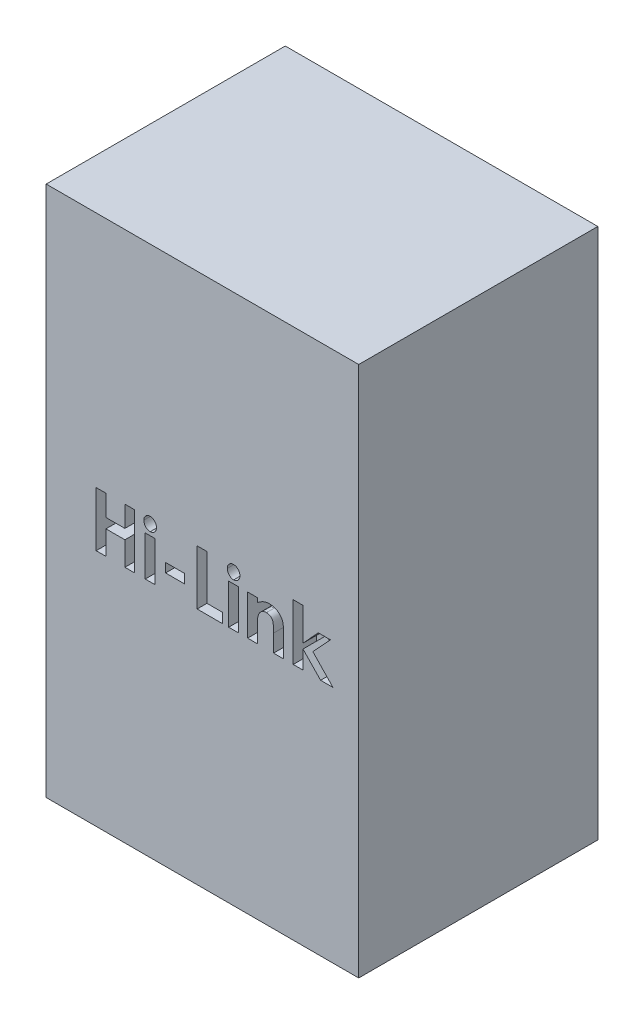
SolidWorks part; units mm, degrees
ref_plane "Plano frontal" through (0, 0, 0) normal (0, 0, 1) x (1, 0, 0)
ref_plane "Plano superior" through (0, 0, 0) normal (0, 1, 0) x (1, 0, 0)
ref_plane "Plano direito" through (0, 0, 0) normal (1, 0, 0) x (0, 0, -1)
sketch "Esboço1" plane through (0, 0, 0) normal (0, 0, 1) x (1, 0, 0)
  line L1 (0, 0) -> (-20, 0)
  line L2 (0, 0) -> (0, 34)
  line L3 (0, 34) -> (-20, 34)
  line L4 (-20, 0) -> (-20, 34)
  dimension "D1" = 20
  dimension "D2" = 34
extrude "Ressalto-extrusão1" add sketch "Esboço1" along normal blind 15.3
sketch "Esboço2" plane through (0, 0, 15.3) normal (0, 0, 1) x (1, 0, 0)
  text T0 "Hi-Link" font "Century Gothic" height 3.5
extrude "Corte-extrusão1" cut sketch "Esboço2" against normal blind 1.5
